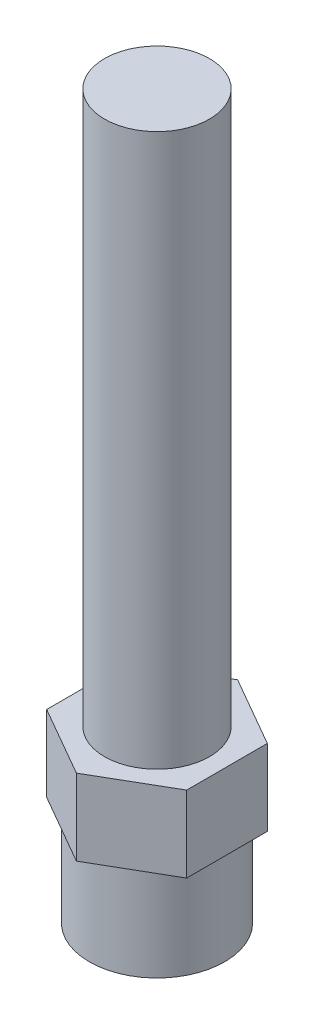
SolidWorks part; units mm, degrees
ref_plane "Front" through (0, 0, 0) normal (0, 0, 1) x (1, 0, 0)
ref_plane "Top" through (0, 0, 0) normal (0, 1, 0) x (1, 0, 0)
ref_plane "Right" through (0, 0, 0) normal (1, 0, 0) x (0, 0, -1)
sketch "Sketch1" plane through (0, 0, 0) normal (0, 1, 0) x (1, 0, 0)
  circle A0 centre (0, 0) radius 6.125
  dimension "D1" = 12.25
extrude "Boss-Extrude1" add sketch "Sketch1" along normal blind 8.5
sketch "Sketch2" plane through (0, 8.5, 0) normal (0, 1, 0) x (1, 0, 0)
  line L1 (6.3355, -3.645) -> (6.3244, 3.6642)
  line L2 (6.3244, 3.6642) -> (-0.0111, 7.3092)
  line L3 (-0.0111, 7.3092) -> (-6.3355, 3.645)
  line L4 (-6.3355, 3.645) -> (-6.3244, -3.6642)
  line L5 (-6.3244, -3.6642) -> (0.0111, -7.3092)
  line L6 (0.0111, -7.3092) -> (6.3355, -3.645)
  circle A0 centre (0, 0) radius 6.33 construction
  dimension "D1" = 12.66
extrude "Boss-Extrude2" add sketch "Sketch2" along normal blind 6.9
sketch "Sketch3" plane through (0, 15.4, 0) normal (0, 1, 0) x (1, 0, 0)
  circle A0 centre (0, 0) radius 4.75
  dimension "D1" = 9.5
extrude "Boss-Extrude3" add sketch "Sketch3" along normal blind 50
